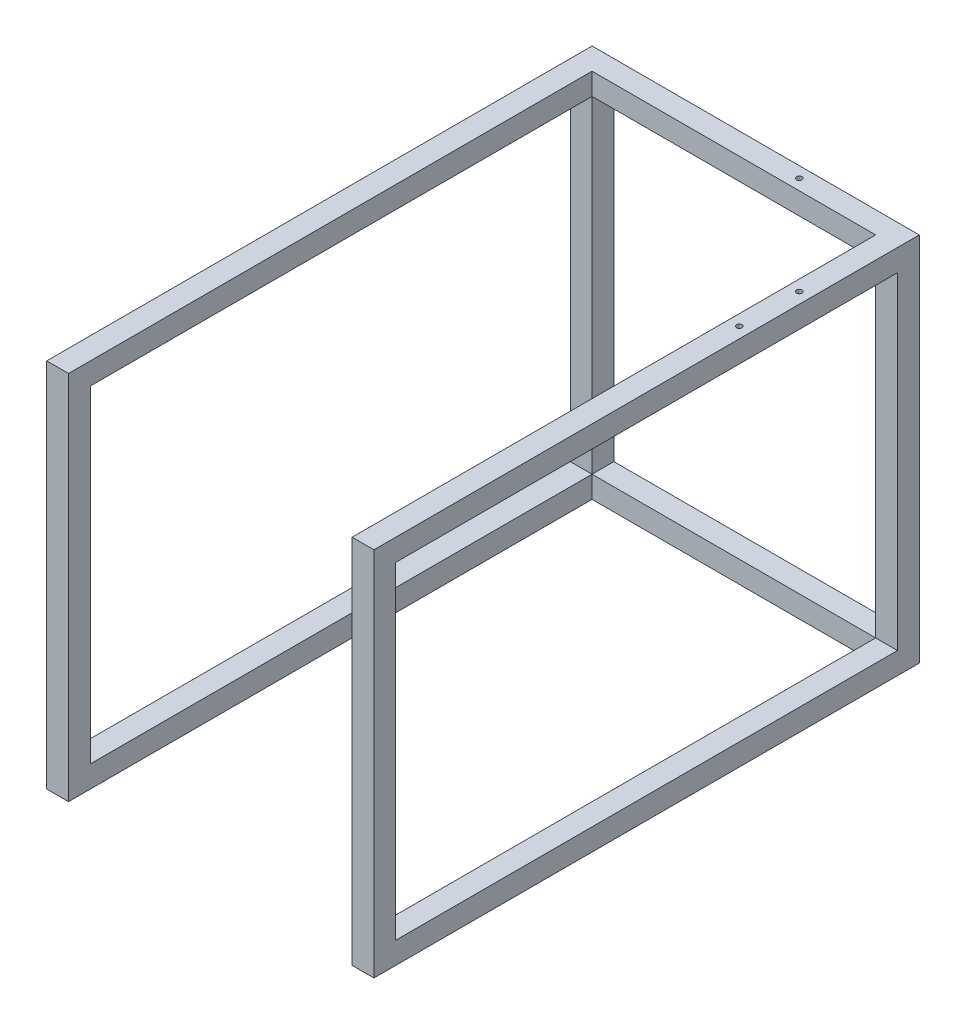
SolidWorks part; units mm, degrees
ref_plane "Front Plane" through (0, 0, 0) normal (0, 0, 1) x (1, 0, 0)
ref_plane "Top Plane" through (0, 0, 0) normal (0, 1, 0) x (1, 0, 0)
ref_plane "Right Plane" through (0, 0, 0) normal (1, 0, 0) x (0, 0, -1)
sketch "Sketch2" plane through (0, 0, 0) normal (0, 1, 0) x (1, 0, 0)
  line L1 (750, 1250) -> (-750, 1250)
  line L2 (750, 1250) -> (750, -1250)
  line L4 (-750, 1250) -> (-750, -1250)
  line L5 (750, 1250) -> (-750, -1250) construction
  line L6 (750, -1250) -> (-750, 1250) construction
  point P0 (0, 0)
  dimension "D1" = 2500
  dimension "D2" = 1500
extrude "Extrude-Thin1" add sketch "Sketch2" along normal blind 100 thin thin type one direction wall 100
sketch "Sketch3" plane through (0, 100, 0) normal (0, 1, 0) x (1, 0, 0)
  line L0 (-650, 1150) -> (-750, 1150)
  line L1 (-650, 1150) -> (-650, 1250)
  line L2 (650, 1150) -> (750, 1150)
  line L3 (650, 1150) -> (650, 1250)
  line L4 (-750, -1150) -> (-650, -1150)
  line L5 (650, -1150) -> (750, -1150)
  line L8 (650, 1150) -> (650, -1250)
  line L9 (650, -1250) -> (750, -1250)
  line L10 (750, -1250) -> (750, 1250)
  line L11 (750, 1250) -> (-750, 1250)
  line L12 (-750, 1250) -> (-750, -1250)
  line L13 (-750, -1250) -> (-650, -1250)
  line L14 (-650, -1250) -> (-650, 1150)
  line L15 (-650, 1150) -> (650, 1150)
  line L16 (650, 1150) -> (650, -1250)
  line L17 (650, -1250) -> (750, -1250)
  line L18 (750, -1250) -> (750, 1250)
  line L19 (750, 1250) -> (-750, 1250)
  line L20 (-750, 1250) -> (-750, -1250)
  line L21 (-750, -1250) -> (-650, -1250)
  line L22 (-650, -1250) -> (-650, 1150)
  line L23 (-650, 1150) -> (650, 1150)
  line M10 (650, 1150) -> (650, -1250)
  line M11 (650, -1250) -> (750, -1250)
  line M12 (750, -1250) -> (750, 1250)
  line M13 (750, 1250) -> (-750, 1250)
  line M14 (-750, 1250) -> (-750, -1250)
  line M15 (-750, -1250) -> (-650, -1250)
  line M16 (-650, -1250) -> (-650, 1150)
  dimension "D2" = 100
  dimension "D1" = 0
extrude "Boss-Extrude1" add sketch "Sketch3" along normal blind 1500 contours L3 L2 M12 M13 | L0 L1 M13 M14 | L4 M14 M15 M16 | L5 M10 M11 M12
sketch "Sketch5" plane through (0, 1600, 0) normal (0, 1, 0) x (1, 0, 0)
  line L0 (750, 1250) -> (650, 1250) construction
  line L1 (750, 1150) -> (750, 1250) construction
  line L2 (650, -1250) -> (750, -1250) construction
  line L3 (750, -1250) -> (750, -1150) construction
  line L4 (-750, 1150) -> (-650, 1150)
  line L5 (-650, 1150) -> (-650, 1250)
  line L6 (-650, 1250) -> (-750, 1250)
  line L7 (-750, 1250) -> (-750, 1150)
  line L8 (-750, 1150) -> (-650, 1150)
  line L9 (-650, 1150) -> (-650, 1250)
  line L10 (-650, 1250) -> (-750, 1250)
  line L11 (-750, 1250) -> (-750, 1150)
  line L12 (650, 1150) -> (650, -1150)
  line L13 (650, -1150) -> (750, -1150)
  line L14 (750, -1150) -> (750, 1150)
  line L15 (750, 1150) -> (650, 1150)
  line L16 (650, 1150) -> (650, -1150)
  line L17 (650, -1150) -> (750, -1150)
  line L18 (750, -1150) -> (750, 1150)
  line L19 (750, 1150) -> (650, 1150)
  line L20 (650, -1150) -> (650, -1250) construction
  line L21 (-750, -1250) -> (-650, -1250) construction
  line L22 (-650, -1250) -> (-650, -1150) construction
  line L23 (-750, -1150) -> (-750, -1250) construction
  line L24 (-750, -1150) -> (-750, 1150) construction
  line L25 (-650, -1150) -> (-650, 1150) construction
  line L26 (-650, 1250) -> (650, 1250) construction
  line L27 (-650, 1150) -> (650, 1150) construction
  line L28 (750, 1250) -> (650, 1250)
  line L29 (750, 1150) -> (750, 1250)
  line L30 (650, -1250) -> (750, -1250)
  line L31 (750, -1250) -> (750, -1150)
  line L32 (650, -1150) -> (650, -1250)
  line L33 (-750, -1250) -> (-650, -1250)
  line L34 (-650, -1250) -> (-650, -1150)
  line L35 (-750, -1150) -> (-750, -1250)
  line L36 (-750, -1150) -> (-750, 1150)
  line L37 (-650, -1150) -> (-650, 1150)
  line L38 (-650, 1250) -> (650, 1250)
  line L39 (-650, 1150) -> (650, 1150)
  line M9 (-750, 1150) -> (-650, 1150)
  line M10 (-650, 1150) -> (-650, 1250)
  line M11 (-650, 1250) -> (-750, 1250)
  line M12 (-750, 1250) -> (-750, 1150)
  dimension "D1" = 0
  dimension "D2" = 0
extrude "Boss-Extrude2" add sketch "Sketch5" along normal blind 100 contours L39 L19 L29 L28 L38 M10 | L34 L37 L36 L35 L33 M9 | M12 M9 M10 M11 | L18 L19 L16 L17 | L17 L32 L30 L31
sketch "Sketch8" plane through (0, 1700, 0) normal (0, 1, 0) x (1, 0, 0)
  line L0 (250, 1200) -> (250, 750)
  line L1 (750, 1250) -> (-750, 1250) construction
  line L2 (700, 750) -> (250, 750)
  line L3 (750, -1250) -> (750, 1250) construction
  line L4 (700, -1250) -> (700, 1250) construction
  line L5 (650, -1250) -> (750, -1250) construction
  line L6 (42.3628, 1150) -> (42.3628, 1250) construction
  line L7 (-650, 1150) -> (650, 1150) construction
  line L8 (42.3628, 1200) -> (750, 1200) construction
  circle A0 centre (700, 750) radius 12.5
  circle A1 centre (250, 1200) radius 12.5
  dimension "D1" = 25
  dimension "D4" = 25
  dimension "D2" = 450
  dimension "D3" = 500
extrude "Cut-Extrude1" cut sketch "Sketch8" against normal up to next
sketch "Sketch9" plane through (0, 1700, 0) normal (0, 1, 0) x (1, 0, 0)
  line L0 (700, 750) -> (700, 475) construction
  circle A0 centre (700, 475) radius 12.5
  dimension "D2" = 25
  dimension "D1" = 275
extrude "Cut-Extrude2" cut sketch "Sketch9" against normal up to next
